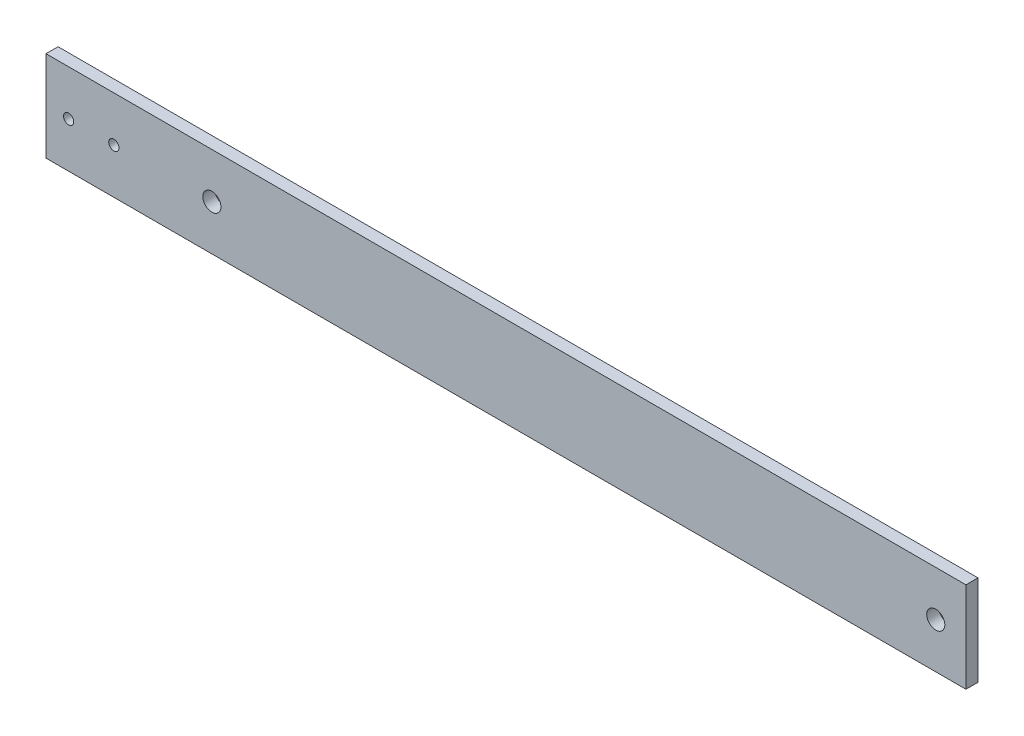
SolidWorks part; units mm, degrees
ref_plane "前视基准面" through (0, 0, 0) normal (0, 0, 1) x (1, 0, 0)
ref_plane "上视基准面" through (0, 0, 0) normal (0, 1, 0) x (1, 0, 0)
ref_plane "右视基准面" through (0, 0, 0) normal (1, 0, 0) x (0, 0, -1)
sketch "草图1" plane through (0, 0, 0) normal (0, 0, 1) x (1, 0, 0)
  line L1 (-305, 30) -> (305, 30)
  line L2 (-305, 30) -> (-305, -30)
  line L3 (-305, -30) -> (305, -30)
  line L4 (305, 30) -> (305, -30)
  line L5 (-305, 30) -> (305, -30) construction
  line L6 (-305, -30) -> (305, 30) construction
  point P0 (0, 0)
  dimension "D1" = 610
  dimension "D2" = 60
extrude "凸台-拉伸1" add sketch "草图1" along normal blind 8
sketch "草图2" plane through (0, 0, 8) normal (0, 0, 1) x (1, 0, 0)
  line L2 (305, -30) -> (305, 30) construction
  point P0 (285, 0)
  point P3 (305, 0)
  dimension "D1" = 0
  dimension "D2" = 20
hole_wizard "大小mm 暗销孔1" positions "3D草图1" profile "草图3" hole size "Ø12.0" standard "GB" end condition through all
sketch3d "3D草图1"
  point P0 (285, 0, 8)
sketch "草图3" plane through (285, 0, 8) normal (1, 0, 0) x (0, -1, 0)
  line L0 (0, 0) -> (0, 8)
  line L1 (0, 8) -> (6, 8)
  line L2 (6, 8) -> (6, 0)
  line L5 (6, 0) -> (0, 0)
  line L11 (0, -6.35) -> (0, 107.95) construction
  dimension "通孔孔直径" = 12
  dimension "通孔孔深度" = 8
pattern_linear "阵列(线性)1" count 2 spacing 480 along (-1, 0, 0) of "大小mm 暗销孔1"
sketch "草图4" plane through (0, 0, 8) normal (0, 0, 1) x (1, 0, 0)
  line L0 (-290, 0) -> (-230, 0)
  line L1 (-305, 30) -> (-305, -30) construction
  line L2 (-305, -30) -> (305, -30) construction
  point P7 (-270, 0)
  point P8 (-250, 0)
  point P9 (0, 0)
  dimension "D1" = 60
  dimension "D2" = 15
  dimension "D3" = 30
hole_wizard "大小mm 暗销孔2" positions "3D草图2" profile "草图5" hole size "Ø1.0" standard "GB" end condition through all
sketch3d "3D草图2"
  point P0 (-290, 0, 8)
sketch "草图5" plane through (-290, 0, 8) normal (1, 0, 0) x (0, -1, 0)
  line L0 (0, 0) -> (0, 8)
  line L1 (0, 8) -> (3.4, 8)
  line L2 (3.4, 8) -> (3.4, 0)
  line L5 (3.4, 0) -> (0, 0)
  line L11 (0, -6.35) -> (0, 107.95) construction
  dimension "通孔孔直径" = 6.8
  dimension "通孔孔深度" = 8
pattern_linear "阵列(线性)2" count 2 spacing 30 along (1, 0, 0) of "大小mm 暗销孔2"
